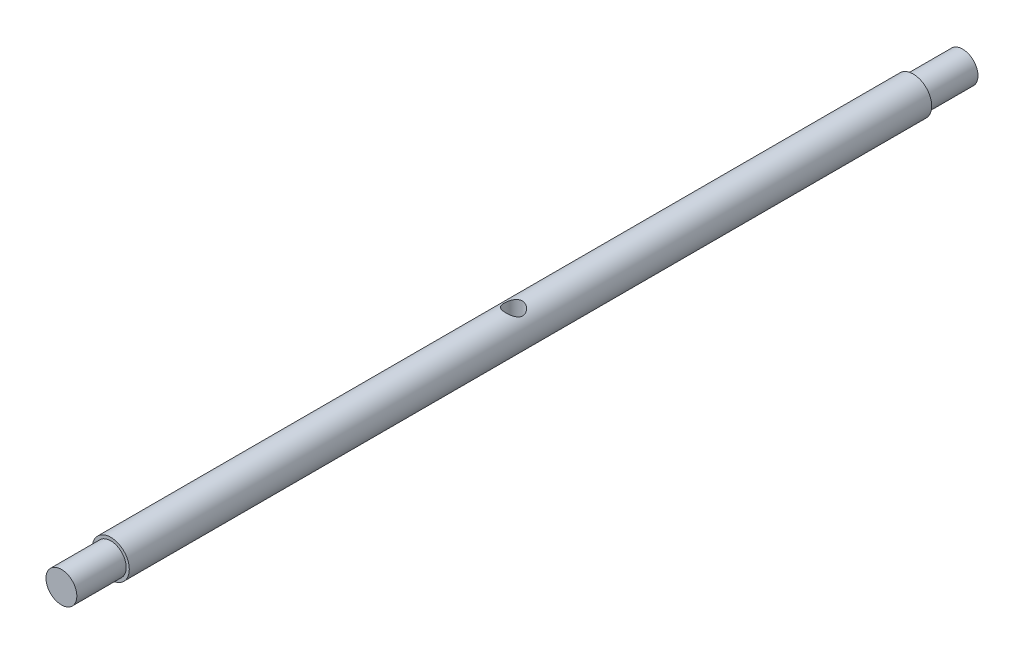
SolidWorks part; units mm, degrees
material "2014 Alloy"
ref_plane "Front Plane" through (0, 0, 0) normal (0, 0, 1) x (1, 0, 0)
ref_plane "Top Plane" through (0, 0, 0) normal (0, 1, 0) x (1, 0, 0)
ref_plane "Right Plane" through (0, 0, 0) normal (1, 0, 0) x (0, 0, -1)
sketch "Sketch1" plane through (0, 0, 0) normal (0, 0, 1) x (1, 0, 0)
  circle A0 centre (0, 0) radius 3
  dimension "D1" = 6
extrude "Boss-Extrude1" add sketch "Sketch1" along normal blind 130
sketch "Sketch2" plane through (0, 0, 130) normal (0, 0, 1) x (1, 0, 0)
  circle A0 centre (0, 0) radius 2.5
  dimension "D1" = 5
extrude "Boss-Extrude2" add sketch "Sketch2" along normal blind 8
sketch "Sketch3" plane through (0, 0, 0) normal (0, 0, -1) x (-1, 0, 0)
  circle A0 centre (0, 0) radius 2.5
  dimension "D1" = 5
extrude "Boss-Extrude3" add sketch "Sketch3" along normal blind 8
sketch "Sketch4" plane through (0, 0, 0) normal (0, 1, 0) x (1, 0, 0)
  line L0 (3, -130) -> (-2.5, 0) construction
  circle A0 centre (0.25, -65) radius 1.5
  point P2 (0.25, -65)
  dimension "D1" = 3
extrude "Cut-Extrude1" cut sketch "Sketch4" against normal up to surface and the other way up to surface up to face at (3, 0, 130) other way up to face at (3, 0, 130)
